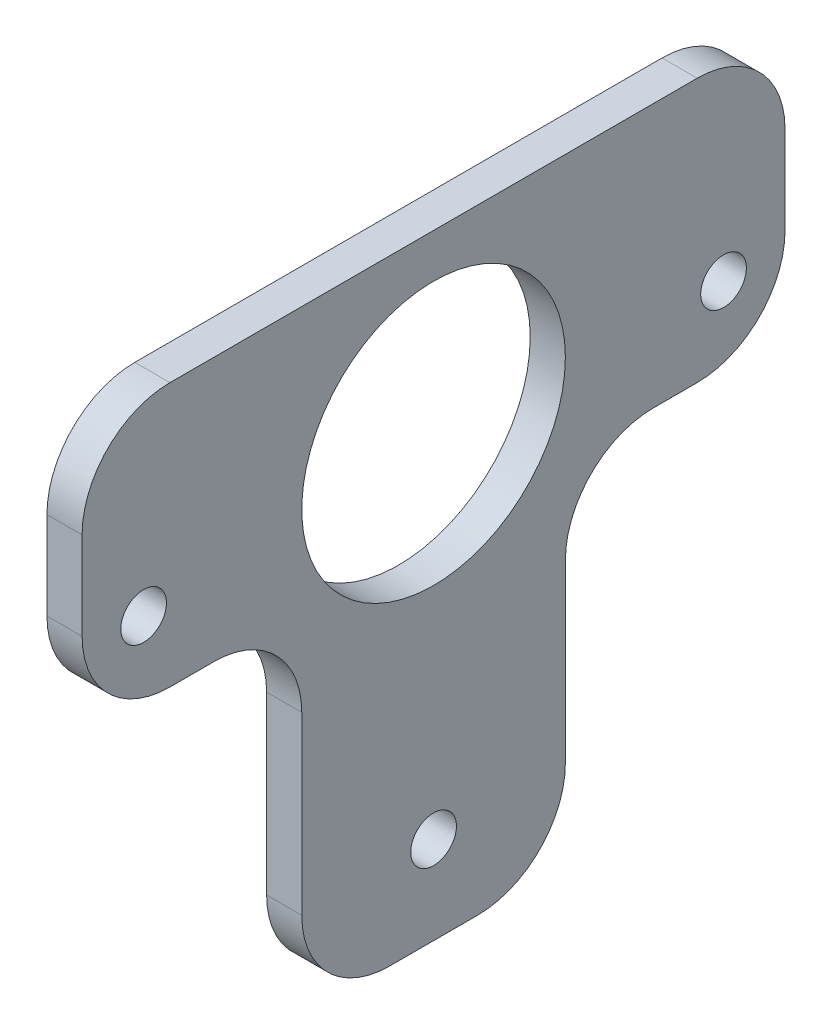
SolidWorks part; units mm, degrees
ref_plane "Front Plane" through (0, 0, 0) normal (0, 0, 1) x (1, 0, 0)
ref_plane "Top Plane" through (0, 0, 0) normal (0, 1, 0) x (1, 0, 0)
ref_plane "Right Plane" through (0, 0, 0) normal (1, 0, 0) x (0, 0, -1)
sketch "Sketch1" plane through (0, 0, 0) normal (1, 0, 0) x (0, 0, -1)
  line L0 (-40, -15) -> (-15, -15)
  line L1 (40, 15) -> (-40, 15)
  line L2 (40, 15) -> (40, -15)
  line L4 (-40, 15) -> (-40, -15)
  line L5 (40, 15) -> (-40, -15) construction
  line L6 (40, -15) -> (-40, 15) construction
  line L7 (-15, -15) -> (-15, -55)
  line L8 (-15, -55) -> (15, -55)
  line L9 (15, -55) -> (15, -15)
  line L10 (15, -15) -> (40, -15)
  point P0 (0, 0)
  dimension "D1" = 80
  dimension "D2" = 30
  dimension "D3" = 55
  dimension "D4" = 30
extrude "Boss-Extrude1" add sketch "Sketch1" along normal blind 4
sketch "Sketch2" plane through (4, 0, 0) normal (1, 0, 0) x (0, 0, -1)
  line L0 (40, 15) -> (-40, 15) construction
  circle A0 centre (0, -5) radius 15
  circle A1 centre (0, -45) radius 2.6
  circle A2 centre (-33, -6.5) radius 2.6
  circle A3 centre (33, -6.5) radius 2.6
  dimension "D1" = 30
  dimension "D2" = 5.2
  dimension "D7" = 20
  dimension "D4" = 33
  dimension "D3" = 66
  dimension "D5" = 40
  dimension "D6" = 1.5
extrude "Cut-Extrude1" cut sketch "Sketch2" against normal blind 5
fillet "Fillet1" radius 10 8 edges at (2, 15, -40) (2, 15, 40) (2, -15, -15) (2, -15, -40) (2, -55, -15) (2, -55, 15) (2, -15, 15) (2, -15, 40)
